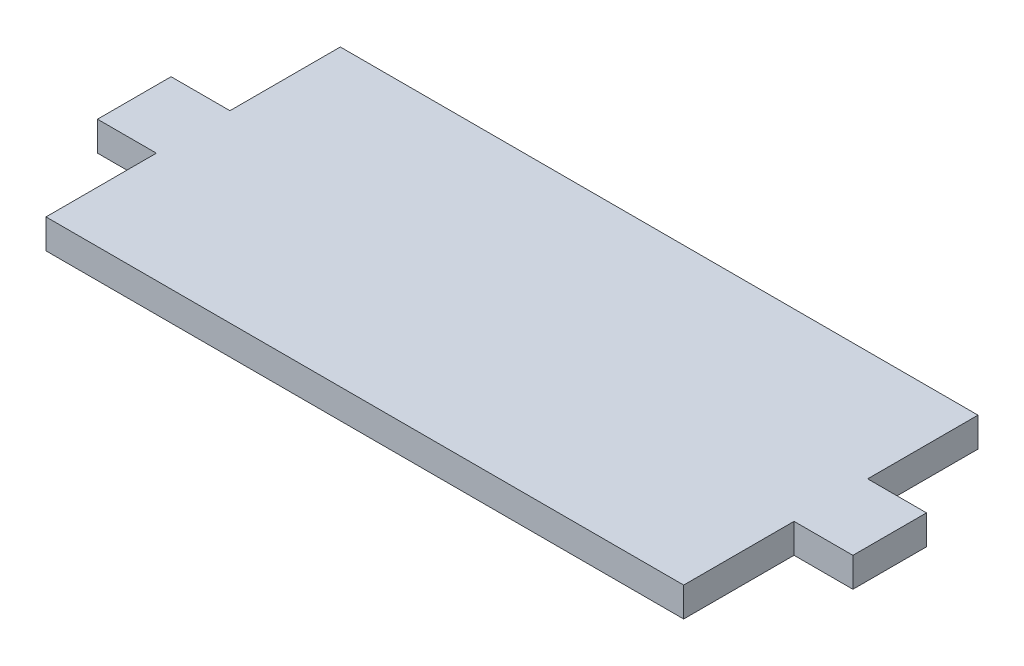
SolidWorks part; units mm, degrees
ref_plane "Ebene vorne" through (0, 0, 0) normal (0, 0, 1) x (1, 0, 0)
ref_plane "Ebene oben" through (0, 0, 0) normal (0, 1, 0) x (1, 0, 0)
ref_plane "Ebene rechts" through (0, 0, 0) normal (1, 0, 0) x (0, 0, -1)
sketch "Skizze1" plane through (0, 0, 0) normal (0, 1, 0) x (1, 0, 0)
  line L0 (0, 30) -> (0, 0) construction
  line L1 (65, 30) -> (-65, 30)
  line L2 (65, 30) -> (65, 7.5)
  line L3 (65, -30) -> (-65, -30)
  line L4 (-65, 30) -> (-65, 7.5)
  line L5 (65, 30) -> (-65, -30) construction
  line L6 (65, -30) -> (-65, 30) construction
  line L7 (0, 0) -> (65, 0) construction
  line L9 (65, -7.5) -> (77, -7.5)
  line L10 (77, -7.5) -> (77, 7.5)
  line L11 (65, 7.5) -> (77, 7.5)
  line L12 (65, -7.5) -> (65, -30)
  line L13 (-65, -7.5) -> (-77, -7.5)
  line L14 (-77, -7.5) -> (-77, 7.5)
  line L15 (-65, 7.5) -> (-77, 7.5)
  line L16 (-65, -7.5) -> (-65, -30)
  point P0 (0, 0)
  point P13 (77, 0)
  dimension "D1" = 60
  dimension "D2" = 130
  dimension "D3" = 12
  dimension "D4" = 15
extrude "Grundplatte" add sketch "Skizze1" along normal blind 6
sketch "Skizze2" [suppressed] plane through (0, 6, 0) normal (0, 1, 0) x (1, 0, 0)
  line L0 (-65, 7.5) -> (-65, 0) construction
  line L1 (-65, 0) -> (-46.4286, 0) construction
  line L2 (-46.4286, 0) -> (-27.8571, 0) construction
  line L3 (-27.8571, 0) -> (-9.2857, 0) construction
  line L4 (-9.2857, 0) -> (9.2857, 0) construction
  line L5 (9.2857, 0) -> (27.8571, 0) construction
  line L6 (27.8571, 0) -> (46.4286, 0) construction
  line L7 (46.4286, 0) -> (65, 0) construction
  line L8 (65, 0) -> (65, 7.5) construction
  circle A0 centre (-46.4286, 0) radius 3.6
  circle A1 centre (-27.8571, 0) radius 3.6
  circle A2 centre (-9.2857, 0) radius 3.6
  circle A3 centre (9.2857, 0) radius 3.6
  circle A4 centre (27.8571, 0) radius 3.6
  circle A5 centre (46.4286, 0) radius 3.6
  dimension "D1" = 7.2
extrude "Schnitt-Linear austragen1" [suppressed] cut sketch "Skizze2" against normal blind 6
sketch "Skizze3" [suppressed] plane through (0, 6, 0) normal (0, 1, 0) x (1, 0, 0)
  line L0 (-65, 7.5) -> (-65, 0) construction
  line L1 (-65, 0) -> (-46.4286, 0) construction
  line L2 (-46.4286, 0) -> (-27.8571, 0) construction
  line L3 (-27.8571, 0) -> (-9.2857, 0) construction
  line L4 (-9.2857, 0) -> (9.2857, 0) construction
  line L5 (9.2857, 0) -> (27.8571, 0) construction
  line L6 (27.8571, 0) -> (46.4286, 0) construction
  line L7 (46.4286, 0) -> (65, 0) construction
  line L8 (65, 0) -> (65, 7.5) construction
  line L10 (-33.8571, 2.5) -> (-21.8571, 2.5)
  line L15 (-33.8571, 2.5) -> (-33.8571, -2.5)
  line L16 (-33.8571, -2.5) -> (-21.8571, -2.5)
  line L21 (-21.8571, 2.5) -> (-21.8571, -2.5)
  line L22 (-33.8571, 2.5) -> (-21.8571, -2.5) construction
  line L23 (-33.8571, -2.5) -> (-21.8571, 2.5) construction
  line L24 (-15.2857, 1.5) -> (-3.2857, 1.5)
  line L25 (-15.2857, 1.5) -> (-15.2857, -1.5)
  line L26 (-15.2857, -1.5) -> (-3.2857, -1.5)
  line L27 (-3.2857, 1.5) -> (-3.2857, -1.5)
  line L28 (-15.2857, 1.5) -> (-3.2857, -1.5) construction
  line L29 (-15.2857, -1.5) -> (-3.2857, 1.5) construction
  line L30 (3.2857, 1.5) -> (15.2857, 1.5)
  line L31 (3.2857, 1.5) -> (3.2857, -1.5)
  line L32 (3.2857, -1.5) -> (15.2857, -1.5)
  line L33 (15.2857, 1.5) -> (15.2857, -1.5)
  line L34 (3.2857, 1.5) -> (15.2857, -1.5) construction
  line L35 (3.2857, -1.5) -> (15.2857, 1.5) construction
  line L36 (25.3571, 2.5) -> (30.3571, 2.5)
  line L37 (25.3571, 2.5) -> (25.3571, -2.5)
  line L38 (25.3571, -2.5) -> (30.3571, -2.5)
  line L39 (30.3571, 2.5) -> (30.3571, -2.5)
  line L40 (25.3571, 2.5) -> (30.3571, -2.5) construction
  line L41 (25.3571, -2.5) -> (30.3571, 2.5) construction
  line L42 (43.9286, 2.5) -> (48.9286, 2.5)
  line L43 (43.9286, 2.5) -> (43.9286, -2.5)
  line L44 (43.9286, -2.5) -> (48.9286, -2.5)
  line L45 (48.9286, 2.5) -> (48.9286, -2.5)
  line L46 (43.9286, 2.5) -> (48.9286, -2.5) construction
  line L47 (43.9286, -2.5) -> (48.9286, 2.5) construction
  circle A3 centre (-46.4286, 0) radius 2.5
  dimension "D1" = 5
  dimension "D2" = 12
  dimension "D3" = 5
  dimension "D4" = 12
  dimension "D5" = 3
  dimension "D6" = 12
  dimension "D7" = 3
  dimension "D8" = 5
  dimension "D9" = 5
  dimension "D10" = 5
  dimension "D11" = 5
extrude "Schnitt-Linear austragen2" [suppressed] cut sketch "Skizze3" against normal blind 6
